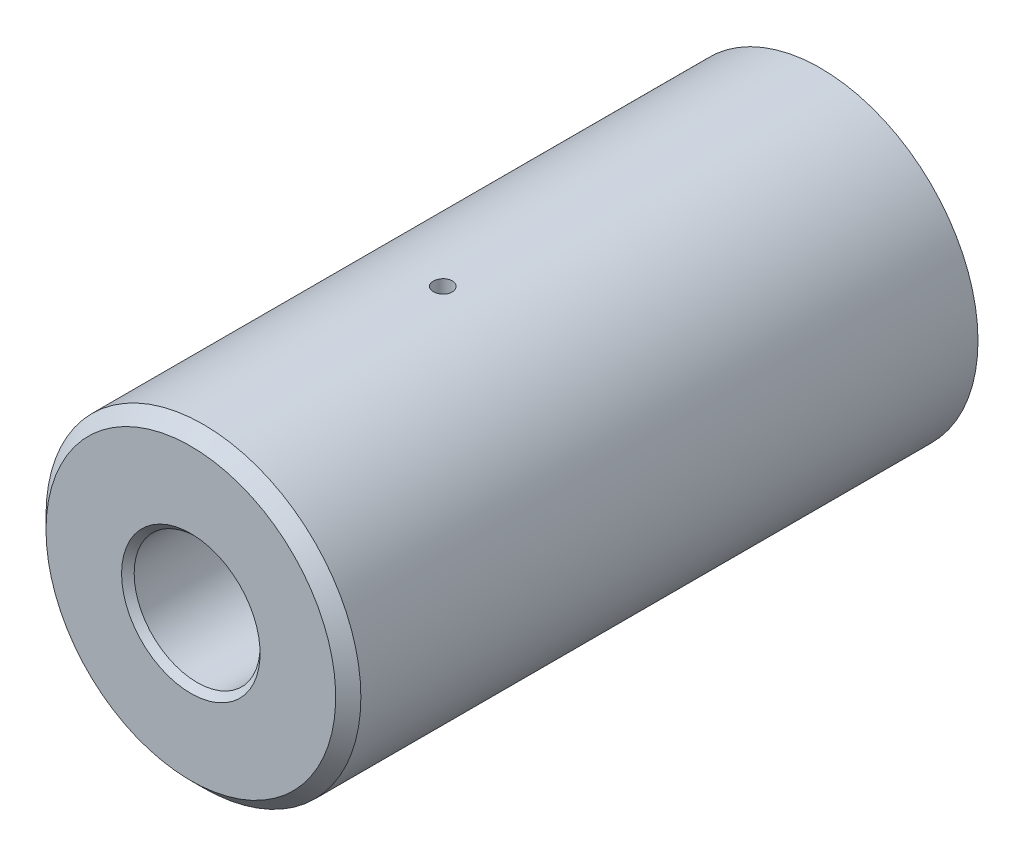
SolidWorks part; units mm, degrees
ref_plane "Piano frontale" through (0, 0, 0) normal (0, 0, 1) x (1, 0, 0)
ref_plane "Piano superiore" through (0, 0, 0) normal (0, 1, 0) x (1, 0, 0)
ref_plane "Piano destro" through (0, 0, 0) normal (1, 0, 0) x (0, 0, -1)
sketch "Schizzo1" plane through (0, 0, 0) normal (1, 0, 0) x (0, 0, -1)
  line L6 (-55.3467, 0) -> (60.0246, 0) construction
  line L7 (-45.8372, 25) -> (54.1628, 25)
  line L8 (-45.8372, 25) -> (-45.8372, 10)
  line L9 (-45.8372, 10) -> (-20.8372, 10)
  line L13 (14.1628, 15) -> (14.1628, 18)
  line L14 (14.1628, 18) -> (19.1628, 18)
  line L15 (19.1628, 18) -> (19.1628, 15)
  line L16 (19.1628, 15) -> (54.1628, 15)
  line L17 (54.1628, 15) -> (54.1628, 25)
  line L18 (14.1628, 15) -> (14.1628, 0)
  line L19 (19.1628, 15) -> (19.1628, 0)
  line L20 (14.1628, 15) -> (-20.8372, 15)
  line L21 (-20.8372, 15) -> (-20.8372, 10)
  line L22 (-5.8372, 35.5961) -> (-5.8372, -41.4001) construction
  point P18 (19.1628, 16.5)
  dimension "D1" = 30
  dimension "D2" = 5
  dimension "D3" = 40
  dimension "D4" = 30
  dimension "D5" = 36
  dimension "D6" = 50
  dimension "D7" = 40
  dimension "D8" = 20
  dimension "D9" = 100
revolve "Rivoluzione1" add sketch "Schizzo1" angle 360 about L6
chamfer "Smusso1" distance 1 angle 45 2 edges at (15, 0, -54.1628) (10, 0, 45.8372)
chamfer "Smusso2" distance 2 angle 45 1 edges at (25, 0, 45.8372)
fillet "Raccordo1" radius 2 1 edges at (15, 0, 20.8372)
ref_plane "Piano1" through (0, -25, 0) normal (0, -1, 0) x (-1, 0, 0)
hole_wizard "Foro Ø3.0 (3)-1" positions "Schizzo4" profile "Schizzo5" hole size "Ø3.0" standard "ISO" end condition through all
sketch "Schizzo4" plane through (0, -25, 0) normal (0, -1, 0) x (-1, 0, 0)
  line L0 (-40.5136, -5.8372) -> (38.8257, -5.8372) construction
  line L2 (25, 54.1628) -> (-25, 54.1628) construction
  point P7 (0, -5.8372)
  dimension "D1" = 60
sketch "Schizzo5" plane through (0, -25, 5.8372) normal (1, 0, 0) x (0, 0, -1)
  line L0 (0, 0) -> (0, 50)
  line L1 (0, 50) -> (1.5, 50)
  line L2 (1.5, 50) -> (1.5, 0)
  line L5 (1.5, 0) -> (0, 0)
  line L11 (0, -6.35) -> (0, 107.95) construction
  dimension "Thru Hole Dia." = 3
  dimension "Thru Hole Depth" = 50
